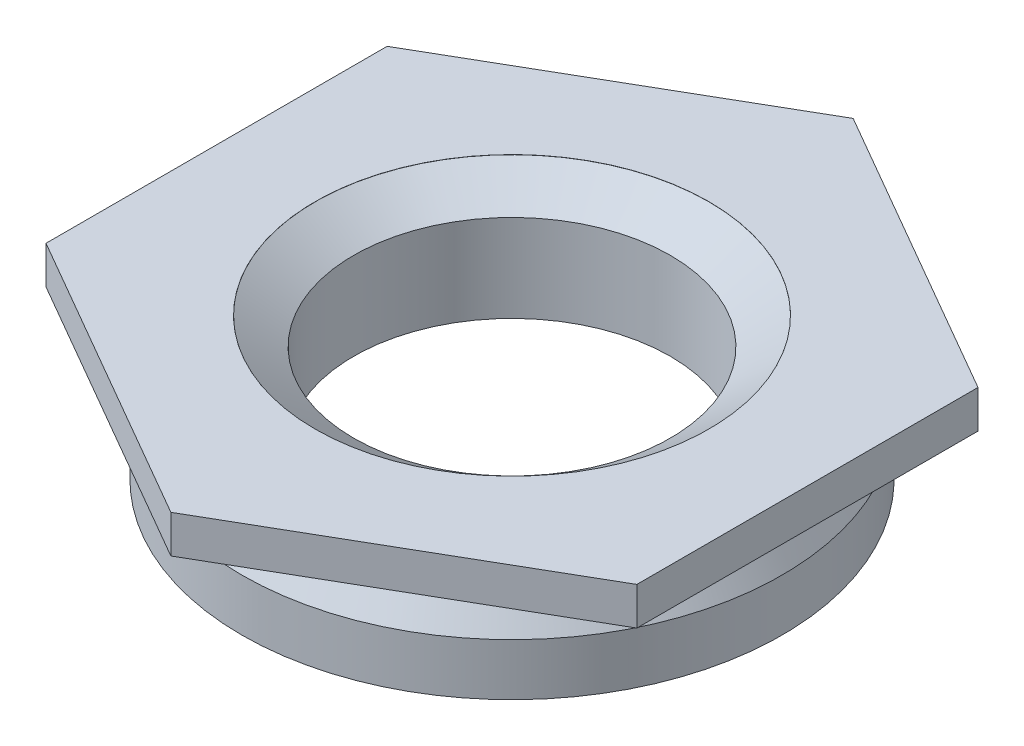
SolidWorks part; units mm, degrees
revolve "Body" add sketch "BodySke"
sketch "BodySke" plane through (0, 0, 0) normal (0, 0, 1) x (1, 0, 0)
  line L0 (4.0481, 0) -> (5.5118, 0)
  line L1 (5.5118, 0) -> (5.5118, 0.6096)
  line L2 (5.5118, 0.6096) -> (2.5527, 0.6096)
  line L3 (2.5527, 0.6096) -> (2.5527, -1.6764)
  line L4 (2.5527, -1.6764) -> (4.3561, -1.6764)
  line L5 (4.3561, -1.6764) -> (4.3561, -0.8382)
  line L6 (4.3561, -0.8382) -> (4.0481, -0.3048)
  line L7 (1.016, 1.27) -> (3.6522, 1.27) construction
  line L9 (0, 0) -> (0, 15.24) construction
  line L10 (4.0481, -0.3048) -> (4.0481, 0)
  dimension "E_dia" = 11.0236
  dimension "C_dia" = 8.7122
  dimension "A_ht" = 1.6764
  dimension "Thread_min" = 5.1054
  dimension "C_len" = 0.8382
  dimension "Clinching_ht" = 0.3048
  dimension "D1" = 60
  dimension "Advance" = 1.27
  dimension "Thickness" = 2.286
cosmetic thread "ThreadCosmetic" [suppressed]
revolve "EndChamfer" cut sketch "EndChamferSke" angle 360 about L0
sketch "EndChamferSke" plane through (0, 0, 0) normal (0, 0, 1) x (1, 0, 0)
  line L0 (0, -2.54) -> (0, 7.62) construction
  line L1 (0, 0) -> (0, 15.24) construction
  line L2 (3.175, -1.9304) -> (3.175, -1.6739)
  line L3 (3.175, -1.6739) -> (2.5527, -1.2383)
  line L4 (2.5527, -1.2383) -> (2.5527, -1.9304)
  line L5 (2.5527, -1.9304) -> (3.175, -1.9304)
  line L6 (3.175, 0.6071) -> (2.5527, 0.1715)
  line L7 (3.175, 0.6071) -> (3.175, 0.8636)
  line L8 (2.5527, 0.1715) -> (2.5527, 0.8636)
  line L9 (3.175, 0.8636) -> (2.5527, 0.8636)
  line L11 (-4.3561, -1.6764) -> (4.3561, -1.6764) construction
  line L12 (5.5118, 0.6096) -> (-5.5118, 0.6096) construction
  dimension "Thread_min" = 5.1054
  dimension "Thread_nominal" = 6.35
  dimension "D1" = 0.254
  dimension "D2" = 34.99
  dimension "D3" = 0.254
ref_plane "Plane1" through (0, 0, 0) normal (0, 0, 1) x (1, 0, 0)
ref_plane "Plane2" through (0, 0, 0) normal (0, 1, 0) x (1, 0, 0)
ref_plane "Plane3" through (0, 0, 0) normal (1, 0, 0) x (0, 0, -1)
ref_plane "Plane4" through (0, -0.5486, 0) normal (0, 1, 0) x (-1, 0, 0)
sketch "ThdSchSke" plane through (0, 0, 0) normal (0, 0, 1) x (1, 0, 0)
  line L0 (0, -5.08) -> (0, 7.62) construction
  line L1 (0, 0) -> (0, 15.24) construction
  line L2 (0, -1.6739) -> (3.175, -1.6739) construction
  line L4 (3.175, -1.6739) -> (2.5527, -1.2381)
  line L6 (3.175, -1.6739) -> (2.5527, -2.1096)
  line L7 (2.5527, -1.2381) -> (2.5527, -2.1096)
  line L8 (3.175, -1.6739) -> (-3.175, -1.6739) construction
  dimension "Thread_min" = 5.1054
  dimension "Thread_nominal" = 6.35
revolve "ThreadSchematic" [suppressed] cut sketch "ThdSchSke" angle 360 about L0
pattern_linear "ThdSchPat" [suppressed]
sketch "HexDieSke" plane through (0, 0.6096, 0) normal (0, 1, 0) x (-1, 0, 0)
  line L0 (0, 5.4993) -> (4.7625, 2.7496)
  line L1 (4.7625, 2.7496) -> (4.7625, -2.7496)
  line L2 (4.7625, -2.7496) -> (0, -5.4993)
  line L3 (0, -5.4993) -> (-4.7625, -2.7496)
  line L4 (-4.7625, -2.7496) -> (-4.7625, 2.7496)
  line L5 (-4.7625, 2.7496) -> (0, 5.4993)
  circle A1 centre (0, 0) radius 4.7625 construction
  circle A2 centre (0, 0) radius 5.4993 construction
  circle A3 centre (0, 0) radius 5.5372
  dimension "Width_across_flats" = 9.525
  dimension "OD" = 11.0744
extrude "HexDie" cut sketch "HexDieSke" against normal blind 0.6096
equation "' \"Thickness@BodySke\" = 0.09"
equation "' \"C_dia@BodySke\" = 0.343"
equation "' \"Width_across_flats@HexDieSke\" = 0.375"
equation "' \"Advance@BodySke\" = 0.05"
equation "' \"Thread_min@BodySke\" = 0.201"
equation "' \"Thread_nominal@ThreadCosmetic\" = 0.25"
equation "\"OD@HexDieSke\" =  \"Width_across_flats@HexDieSke\" * 1.16 + 0.001"
equation "\"E_dia@BodySke\" = \"Width_across_flats@HexDieSke\" * 1.16 - 0.001"
equation "\"A_ht@BodySke\" = \"Thickness@BodySke\" - 0.06 * 0.4"
equation "\"Depth@HexDie\" = \"Thickness@BodySke\" - \"A_ht@BodySke\""
equation "\"Clinching_ht@BodySke\" = 0.012 '  \"Thickness@BodySke\" - 0.06 * 0.8"
equation "\"C_len@BodySke\" =  \"Thickness@BodySke\" - 0.057"
equation "\"Thread_nominal@EndChamferSke\" = \"Thread_nominal@ThreadCosmetic\""
equation "\"Thread_min@EndChamferSke\" = \"Thread_min@BodySke\""
equation "\"D2@EndChamferSke\" = \"Vee_angle@ThdSchSke\" / 2 - 0.01"
equation "\"Thread_nominal@ThdSchSke\" = \"Thread_nominal@ThreadCosmetic\""
equation "\"Thread_min@ThdSchSke\" = \"Thread_min@BodySke\""
equation "\"Num_threads@ThdSchPat\" = int(  ( \"Thickness@BodySke\" - \"Inset@EndChamferSke\" - \"Inset_far@EndChamferSke\" ) / \"Advance@BodySke\" + 0.999 )  + 1"
equation "\"Advance@ThdSchPat\" = (  \"Thickness@BodySke\" - \"Inset@EndChamferSke\" - \"Inset_far@EndChamferSke\"  ) /  (\"Num_threads@ThdSchPat\" - 1) 'relax it"
